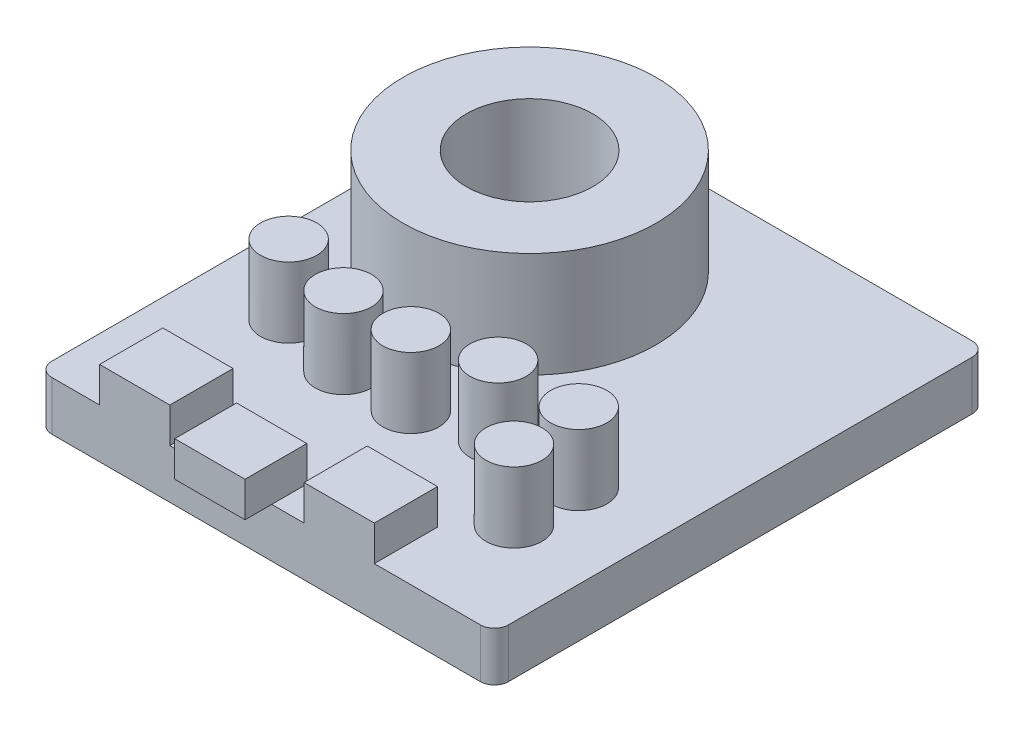
SolidWorks part; units mm, degrees
ref_plane "前视基准面" through (0, 0, 0) normal (0, 0, 1) x (1, 0, 0)
ref_plane "上视基准面" through (0, 0, 0) normal (0, 1, 0) x (1, 0, 0)
ref_plane "右视基准面" through (0, 0, 0) normal (1, 0, 0) x (0, 0, -1)
other "Configuration Table"
sketch "草图1" plane through (0, 0, 0) normal (0, 1, 0) x (1, 0, 0)
  line L1 (-32.5, -35) -> (32.5, -35)
  line L2 (-32.5, -35) -> (-32.5, 35)
  line L3 (-32.5, 35) -> (32.5, 35)
  line L4 (32.5, -35) -> (32.5, 35)
  line L5 (-32.5, -35) -> (32.5, 35) construction
  line L6 (-32.5, 35) -> (32.5, -35) construction
  point P1 (0, 0)
  dimension "D1" = 65
  dimension "D2" = 70
extrude "凸台-拉伸1" add sketch "草图1" along normal blind 7
fillet "圆角1" radius 2 4 edges at (-32.5, 3.5, -35) (32.5, 3.5, -35) (-32.5, 3.5, 35) (32.5, 3.5, 35)
sketch "草图3" plane through (0, 7, 0) normal (0, 1, 0) x (1, 0, 0)
  line L0 (30.5, 35) -> (-30.5, 35) construction
  circle A0 centre (-9.5, 12) radius 18
  circle A1 centre (-9.5, 12) radius 9
  dimension "D3" = 36
  dimension "D4" = 18
  dimension "D1" = 27.5
  dimension "D2" = 5
extrude "凸台-拉伸2" add sketch "草图3" along normal blind 15
sketch "草图4" plane through (0, 7, 0) normal (0, 1, 0) x (1, 0, 0)
  circle A0 centre (-20.6937, -11.0994) radius 4
  circle A1 centre (-10.4409, -13.545) radius 4
  circle A2 centre (9.124, -11.0994) radius 4
  circle A3 centre (20.5996, -20.3175) radius 4
  circle A4 centre (-0.8466, -13.545) radius 4
  circle A5 centre (20.5996, -11.0994) radius 4
  dimension "D1" = 8
extrude "凸台-拉伸3" add sketch "草图4" along normal blind 10
sketch "草图5" plane through (0, 7, 0) normal (0, 1, 0) x (1, 0, 0)
  line L0 (-30.5, -35) -> (30.5, -35) construction
  line L1 (-23.7, -35) -> (-13.7, -35)
  line L2 (-23.7, -35) -> (-23.7, -26)
  line L3 (-23.7, -26) -> (-13.7, -26)
  line L4 (-13.7, -35) -> (-13.7, -26)
  line L5 (-32.5, 33) -> (-32.5, -33) construction
  line L6 (-9.2, -38.8) -> (0.8, -38.8)
  line L7 (-9.2, -38.8) -> (-9.2, -30)
  line L8 (-9.2, -30) -> (0.8, -30)
  line L9 (0.8, -38.8) -> (0.8, -30)
  line L10 (5.4, -35) -> (15.4, -35)
  line L11 (5.4, -35) -> (5.4, -26)
  line L12 (5.4, -26) -> (15.4, -26)
  line L13 (15.4, -35) -> (15.4, -26)
  dimension "D1" = 8.8
  dimension "D2" = 9
  dimension "D3" = 10
  dimension "D4" = 4.5
  dimension "D5" = 3.8
  dimension "D6" = 5
  dimension "D7" = 4.6
extrude "凸台-拉伸4" add sketch "草图5" along normal blind 5
